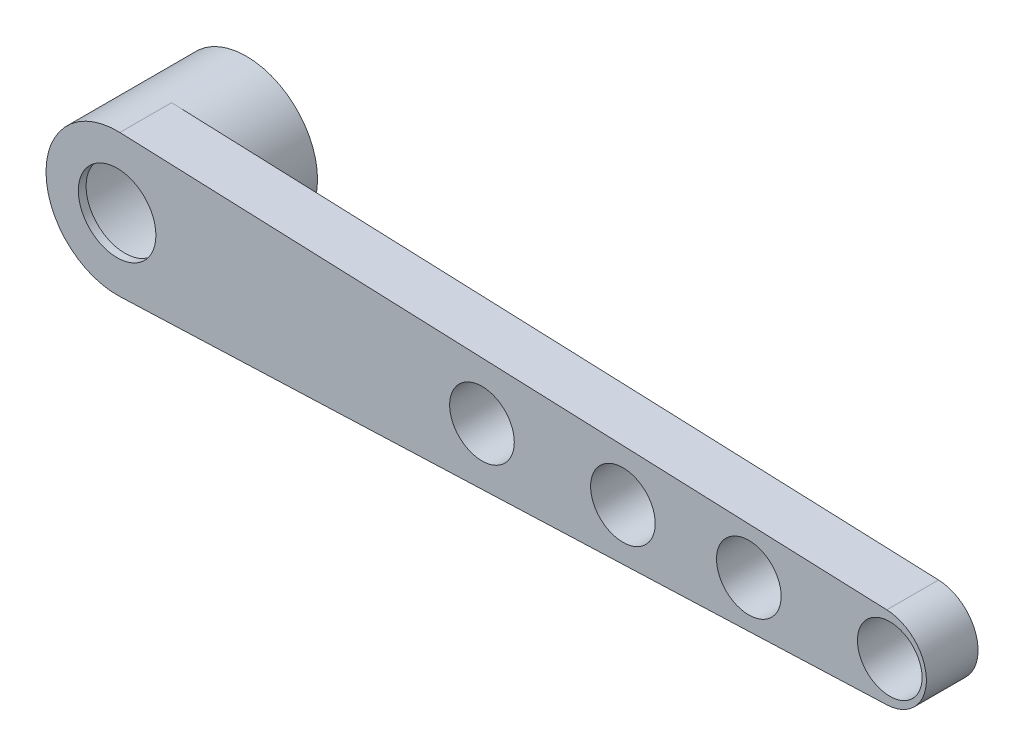
SolidWorks part; units mm, degrees
ref_plane "前视基准面" through (0, 0, 0) normal (0, 0, 1) x (1, 0, 0)
ref_plane "上视基准面" through (0, 0, 0) normal (0, 1, 0) x (1, 0, 0)
ref_plane "右视基准面" through (0, 0, 0) normal (1, 0, 0) x (0, 0, -1)
sketch "草图1" plane through (0, 0, 0) normal (0, 0, 1) x (1, 0, 0)
  circle A0 centre (0, 0) radius 2.75
  dimension "D1" = 5.5
extrude "凸台-拉伸1" add sketch "草图1" along normal blind 5
sketch "草图2" plane through (0, 0, 0) normal (0, 0, -1) x (-1, 0, 0)
  circle A0 centre (0, 0) radius 2.5
  dimension "D1" = 5
extrude "切除-拉伸1" cut sketch "草图2" against normal blind 4.7
sketch "草图3" plane through (0, 0, 5) normal (0, 0, 1) x (1, 0, 0)
  circle A0 centre (0, 0) radius 1.5
  dimension "D1" = 3
extrude "切除-拉伸2" cut sketch "草图3" against normal blind 4.7
sketch "草图4" plane through (0, 0, 5) normal (0, 0, 1) x (1, 0, 0)
  line L0 (0.1072, 2.7479) -> (29.7652, 1.591)
  line L1 (0.1072, -2.7479) -> (29.7652, -1.591)
  arc A0 (29.7652, 1.591) -> (29.7652, -1.591) centre (29.7031, 0) cw
  circle A1 centre (14.11, 0) radius 1.25
  circle A2 centre (24.43, 0) radius 1.25
  circle A3 centre (29.88, 0.0035) radius 1.25
  circle A4 centre (0, 0) radius 2.75 construction
  circle M2 centre (0, 0) radius 2.75
  dimension "D1" = 2.5
  dimension "D2" = 2.5
  dimension "D3" = 2.5
  dimension "D4" = 29.88
  dimension "D5" = 24.43
  dimension "D7" = 2.2
  dimension "D8" = 2.2
extrude "凸台-拉伸3" add sketch "草图4" against normal blind 2 contours A0 L0 L1 A3 A2 A1 M2
sketch "草图5" plane through (0, 0, 5) normal (0, 0, 1) x (1, 0, 0)
  circle A0 centre (19.56, 0) radius 1.25
  dimension "D1" = 2.5
extrude "切除-拉伸3" cut sketch "草图5" against normal blind 10
